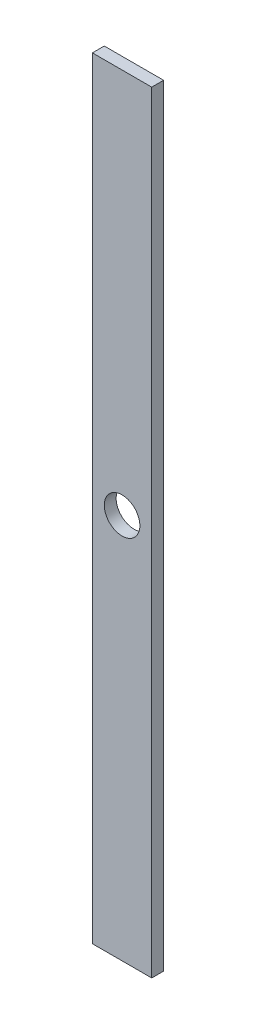
SolidWorks part; units mm, degrees
ref_plane "Plan de face" through (0, 0, 0) normal (0, 0, 1) x (1, 0, 0)
ref_plane "Plan de dessus" through (0, 0, 0) normal (0, 1, 0) x (1, 0, 0)
ref_plane "Plan de droite" through (0, 0, 0) normal (1, 0, 0) x (0, 0, -1)
sketch "Esquisse1" plane through (0, 0, 0) normal (0, 0, 1) x (1, 0, 0)
  line L1 (0, 0) -> (50, 0)
  line L2 (0, 0) -> (0, -650)
  line L3 (0, -650) -> (50, -650)
  line L4 (50, 0) -> (50, -650)
  circle A0 centre (25, -325) radius 15
  dimension "D5" = 30
  dimension "D1" = 50
  dimension "D2" = 650
  dimension "D3" = 25
  dimension "D4" = 325
extrude "Boss.-Extru.1" add sketch "Esquisse1" along normal blind 10
